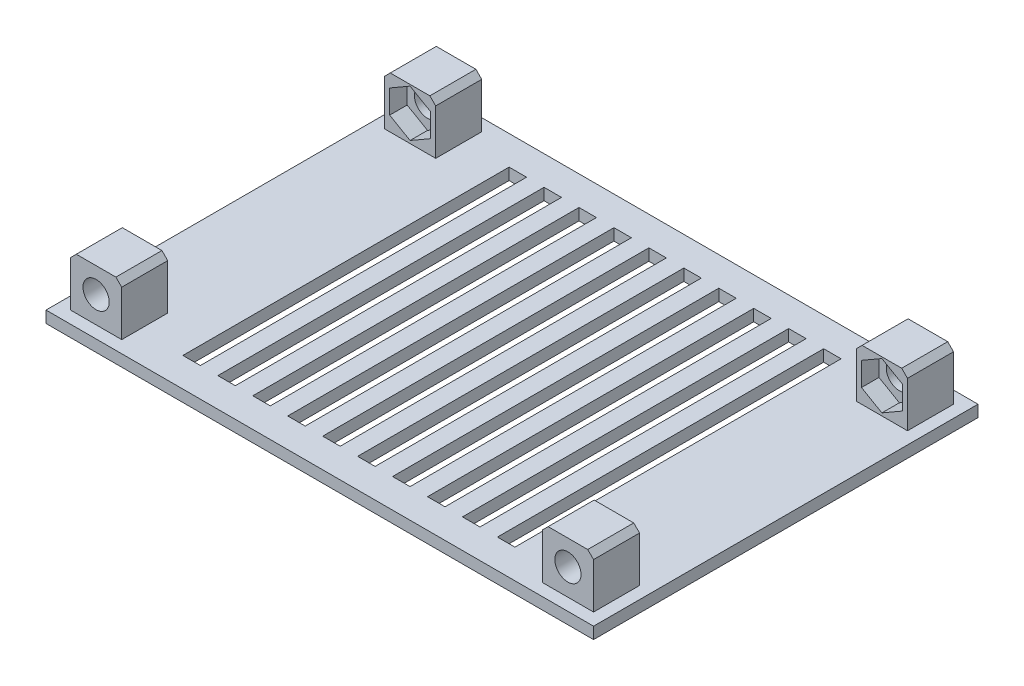
SolidWorks part; units mm, degrees
ref_plane "Front Plane" through (0, 0, 0) normal (0, 0, 1) x (1, 0, 0)
ref_plane "Top Plane" through (0, 0, 0) normal (0, 1, 0) x (1, 0, 0)
ref_plane "Right Plane" through (0, 0, 0) normal (1, 0, 0) x (0, 0, -1)
sketch "Sketch1" plane through (0, 0, 0) normal (0, 1, 0) x (1, 0, 0)
  line L1 (-47, -33) -> (47, -33)
  line L2 (-47, -33) -> (-47, 33)
  line L3 (-47, 33) -> (47, 33)
  line L4 (47, -33) -> (47, 33)
  line L5 (-47, -33) -> (47, 33) construction
  line L6 (-47, 33) -> (47, -33) construction
  point P0 (0, 0)
  dimension "D1" = 94
  dimension "D2" = 66
extrude "Boss-Extrude1" add sketch "Sketch1" along normal blind 2
sketch "Sketch2" plane through (0, 2, 0) normal (0, 1, 0) x (1, 0, 0)
  line L0 (-47, -30.9) -> (47, -30.9) construction
  line L1 (-47, 33) -> (-47, -33) construction
  line L2 (47, -33) -> (47, 33) construction
  line L3 (-47, -33) -> (47, -33) construction
  line L4 (-47, 0) -> (47, 0) construction
  line L5 (-44.9, -30.9) -> (-36.1, -30.9)
  line L6 (-44.9, -30.9) -> (-44.9, -23)
  line L7 (-44.9, -23) -> (-36.1, -23)
  line L8 (-36.1, -30.9) -> (-36.1, -23)
  line L9 (0, 33) -> (0, -33) construction
  line L10 (47, 33) -> (-47, 33) construction
  line L11 (44.9, -23) -> (36.1, -23)
  line L12 (36.1, -30.9) -> (36.1, -23)
  line L13 (44.9, -30.9) -> (36.1, -30.9)
  line L14 (44.9, -30.9) -> (44.9, -23)
  line L15 (44.9, 30.9) -> (44.9, 23)
  line L16 (44.9, 30.9) -> (36.1, 30.9)
  line L17 (36.1, 30.9) -> (36.1, 23)
  line L18 (44.9, 23) -> (36.1, 23)
  line L19 (-44.9, 23) -> (-36.1, 23)
  line L20 (-36.1, 30.9) -> (-36.1, 23)
  line L21 (-44.9, 30.9) -> (-36.1, 30.9)
  line L22 (-44.9, 30.9) -> (-44.9, 23)
  point P12 (-44.9, -26.95)
  dimension "D1" = 2.1
  dimension "D2" = 2.1
  dimension "D3" = 10
  dimension "D4" = 8.8
extrude "Boss-Extrude2" add sketch "Sketch2" along normal blind 8.8
sketch "Sketch3" plane through (0, 0, 30.9) normal (0, 0, 1) x (1, 0, 0)
  line L0 (-47, 2) -> (47, 2) construction
  line L1 (-47, 2) -> (-47, 0) construction
  line L6 (-36.1, 10.8) -> (36.1, 10.8) construction
  line L7 (0, 10.8) -> (0, 0) construction
  circle A0 centre (-40.5, 6.5) radius 2.25
  circle A1 centre (40.5, 6.5) radius 2.25
  dimension "D1" = 4.5
  dimension "D2" = 6.5
  dimension "D3" = 4.5
extrude "Cut-Extrude1" cut sketch "Sketch3" against normal through all
sketch "Sketch5" plane through (0, 0, -23) normal (0, 0, 1) x (1, 0, 0)
  line L1 (-40.5, 10.5415) -> (-44, 8.5207)
  line L2 (-44, 8.5207) -> (-44, 4.4793)
  line L3 (-44, 4.4793) -> (-40.5, 2.4585)
  line L4 (-40.5, 2.4585) -> (-37, 4.4793)
  line L5 (-37, 4.4793) -> (-37, 8.5207)
  line L6 (-37, 8.5207) -> (-40.5, 10.5415)
  circle A0 centre (-40.5, 6.5) radius 3.5 construction
  dimension "D1" = 7
  dimension "D2" = 3.5
extrude "Cut-Extrude2" cut sketch "Sketch5" against normal blind 3
chamfer "Chamfer1" distance 1 angle 45 8 edges at (44.9, 10.8, 26.95) (36.1, 10.8, 26.95) (44.9, 10.8, -26.95) (36.1, 10.8, -26.95) (-36.1, 10.8, 26.95) (-44.9, 10.8, 26.95) (-36.1, 10.8, -26.95) (-44.9, 10.8, -26.95)
mirror "Mirror1" about plane through (0, 0, 0) normal (0, 0, 1) of "Cut-Extrude2"
mirror "Mirror2" about plane through (0, 0, 0) normal (1, 0, 0) of "Mirror1", "Cut-Extrude2"
sketch "Sketch6" plane through (0, 2, 0) normal (0, 1, 0) x (1, 0, 0)
  line L0 (-47, 0) -> (47, 0) construction
  line L3 (-47, 33) -> (-47, -33) construction
  line L5 (47, -33) -> (47, 33) construction
  line L6 (0, 33) -> (0, -33) construction
  line L7 (-4.5, -28) -> (-1.5, -28)
  line L8 (-4.5, -28) -> (-4.5, 28)
  line L9 (-4.5, 28) -> (-1.5, 28)
  line L10 (-1.5, -28) -> (-1.5, 28)
  line L11 (-4.5, -28) -> (-1.5, 28) construction
  line L12 (-4.5, 28) -> (-1.5, -28) construction
  line L13 (47, 33) -> (-47, 33) construction
  line L14 (-47, -33) -> (47, -33) construction
  line L15 (-10.5, -28) -> (-10.5, 28)
  line L16 (-10.5, -28) -> (-7.5, -28)
  line L17 (-7.5, -28) -> (-7.5, 28)
  line L18 (-10.5, 28) -> (-7.5, 28)
  line L19 (-16.5, -28) -> (-16.5, 28)
  line L20 (-16.5, -28) -> (-13.5, -28)
  line L21 (-13.5, -28) -> (-13.5, 28)
  line L22 (-16.5, 28) -> (-13.5, 28)
  line L23 (-22.5, -28) -> (-22.5, 28)
  line L24 (-22.5, -28) -> (-19.5, -28)
  line L25 (-19.5, -28) -> (-19.5, 28)
  line L26 (-22.5, 28) -> (-19.5, 28)
  line L27 (-28.5, -28) -> (-28.5, 28)
  line L28 (-28.5, -28) -> (-25.5, -28)
  line L29 (-25.5, -28) -> (-25.5, 28)
  line L30 (-28.5, 28) -> (-25.5, 28)
  line L31 (4.5, 28) -> (1.5, 28)
  line L32 (1.5, -28) -> (1.5, 28)
  line L33 (4.5, -28) -> (1.5, -28)
  line L34 (4.5, -28) -> (4.5, 28)
  line L35 (10.5, -28) -> (7.5, -28)
  line L36 (7.5, -28) -> (7.5, 28)
  line L37 (10.5, 28) -> (7.5, 28)
  line L38 (10.5, -28) -> (10.5, 28)
  line L39 (16.5, -28) -> (13.5, -28)
  line L40 (13.5, -28) -> (13.5, 28)
  line L41 (16.5, 28) -> (13.5, 28)
  line L42 (16.5, -28) -> (16.5, 28)
  line L43 (22.5, -28) -> (19.5, -28)
  line L44 (19.5, -28) -> (19.5, 28)
  line L45 (22.5, 28) -> (19.5, 28)
  line L46 (22.5, -28) -> (22.5, 28)
  line L47 (28.5, -28) -> (25.5, -28)
  line L48 (25.5, -28) -> (25.5, 28)
  line L49 (28.5, 28) -> (25.5, 28)
  line L50 (28.5, -28) -> (28.5, 28)
  point P6 (-3, 0)
  dimension "D1" = 3
  dimension "D2" = 1.5
  dimension "D3" = 5
  dimension "D5" = 3
  dimension "D4" = 5
extrude "Cut-Extrude3" cut sketch "Sketch6" against normal up to next
